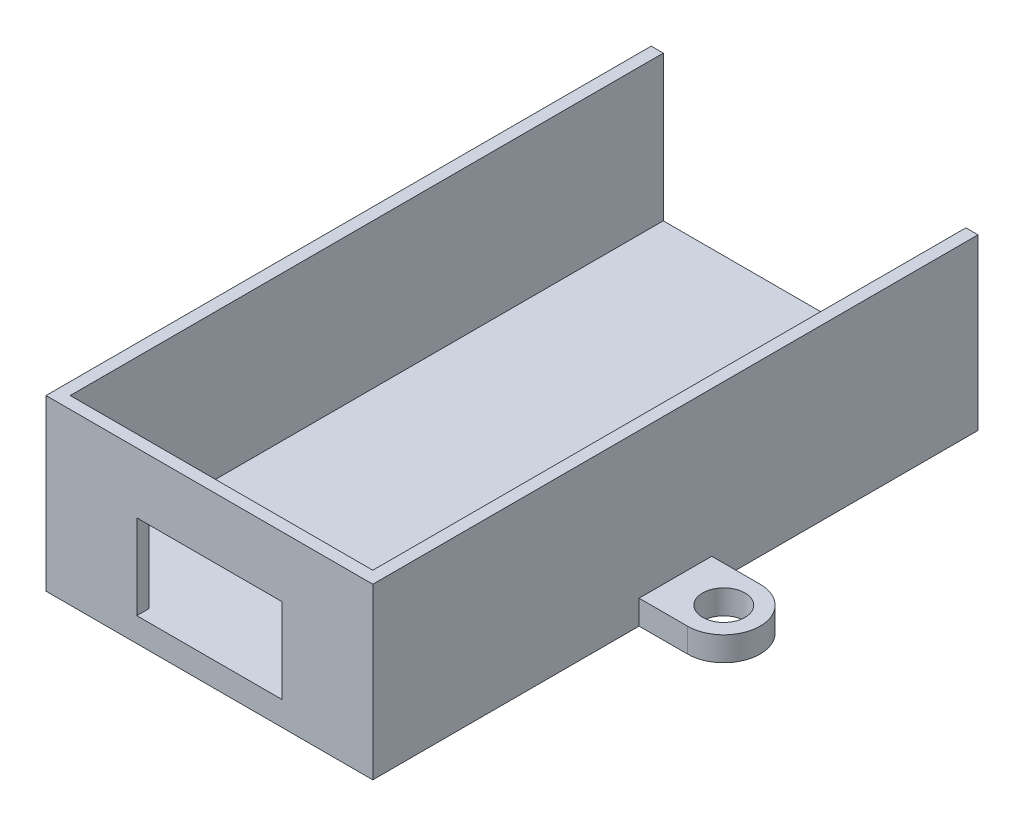
SolidWorks part; units mm, degrees
ref_plane "Front Plane" through (0, 0, 0) normal (0, 0, 1) x (1, 0, 0)
ref_plane "Top Plane" through (0, 0, 0) normal (0, 1, 0) x (1, 0, 0)
ref_plane "Right Plane" through (0, 0, 0) normal (1, 0, 0) x (0, 0, -1)
sketch "Sketch1" plane through (0, 0, 0) normal (0, 1, 0) x (1, 0, 0)
  line L0 (0, 0) -> (0, 9.5111) construction
  line L1 (0, 0) -> (17.5, 0) construction
  line L2 (13.5, -25) -> (13.5, 25)
  line L3 (17.5, 3) -> (13.5, 3)
  line L4 (17.5, -3) -> (13.5, -3)
  line L5 (-17.5, -3) -> (-13.5, -3)
  line L6 (-17.5, 3) -> (-13.5, 3)
  line L7 (-13.5, -25) -> (-13.5, 25)
  line L8 (-13.5, 25) -> (13.5, 25)
  line L9 (-13.5, -25) -> (13.5, -25)
  circle A0 centre (17.5, 0) radius 1.75
  circle A1 centre (17.5, 0) radius 3
  circle A2 centre (-17.5, 0) radius 1.75
  circle A3 centre (-17.5, 0) radius 3
  point P9 (13.5, 0)
  dimension "D1" = 3.5
  dimension "D2" = 6
  dimension "D3" = 35
  dimension "D4" = 27
  dimension "D5" = 50
extrude "Boss-Extrude1" add sketch "Sketch1" along normal blind 2 contours L7 L9 L2 L8 | L6 A3 L5 L7 | A3 A2 | A1 L3 L2 L4 | A1 A0
sketch "Sketch2" plane through (0, 2, 0) normal (0, 1, 0) x (1, 0, 0)
  line L1 (-13.5, 25) -> (-13.5, -25)
  line L2 (-13.5, -25) -> (13.5, -25)
  line L3 (13.5, -25) -> (13.5, 25)
  line L4 (-13.5, 25) -> (-12.5, 25)
  line L5 (-13.5, 25) -> (13.5, 25) construction
  line L6 (-12.5, 25) -> (-12.5, -24)
  line L7 (-12.5, -24) -> (12.5, -24)
  line L8 (12.5, -24) -> (12.5, 25)
  line L9 (12.5, 25) -> (13.5, 25)
  dimension "D1" = 1
  dimension "D2" = 1
  dimension "D3" = 1
extrude "Boss-Extrude2" add sketch "Sketch2" along normal blind 12
sketch "Sketch4" plane through (0, 0, 25) normal (0, 0, 1) x (1, 0, 0)
  line L0 (12.5, 2) -> (-12.5, 2) construction
  line L1 (6, 2) -> (-6, 2)
  line L2 (0, 2) -> (0, 14) construction
  line L3 (-13.5, 14) -> (13.5, 14) construction
  line L4 (-6, 9) -> (6, 9)
  line L5 (6, 9) -> (6, 2)
  line L6 (-6, 9) -> (-6, 2)
  point P11 (0, 9)
  dimension "D1" = 7
  dimension "D2" = 12
extrude "Cut-Extrude1" cut sketch "Sketch4" against normal through all
